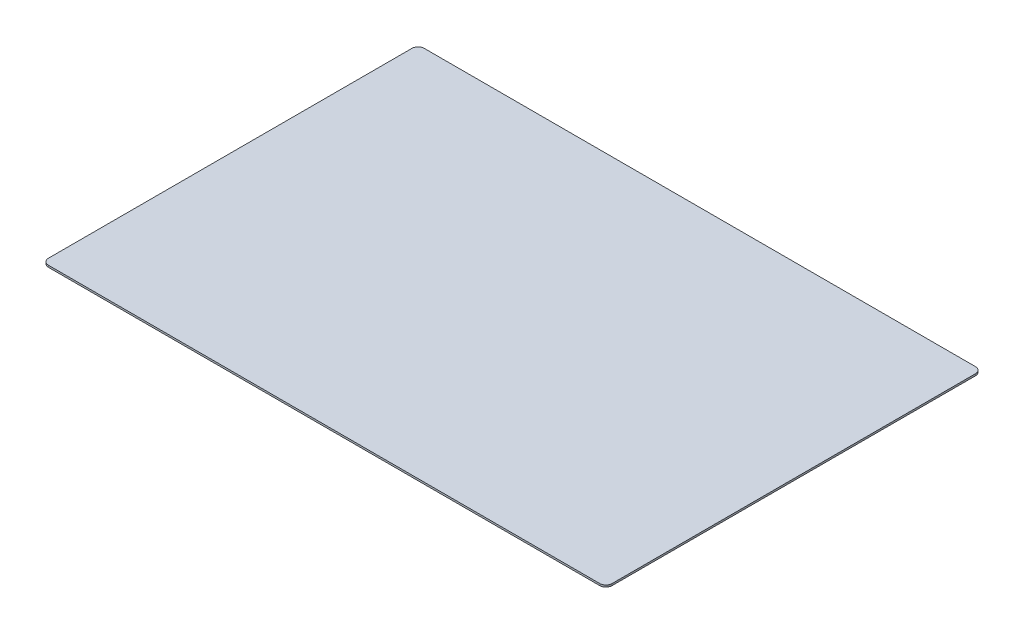
SolidWorks part; units mm, degrees
ref_plane "Front Plane" through (0, 0, 0) normal (0, 0, 1) x (1, 0, 0)
ref_plane "Top Plane" through (0, 0, 0) normal (0, 1, 0) x (1, 0, 0)
ref_plane "Right Plane" through (0, 0, 0) normal (1, 0, 0) x (0, 0, -1)
sketch "Sketch1" plane through (0, 0, 0) normal (0, 1, 0) x (1, 0, 0)
  line L1 (-457.2, 304.8) -> (457.2, 304.8)
  line L2 (-457.2, 304.8) -> (-457.2, -304.8)
  line L3 (-457.2, -304.8) -> (457.2, -304.8)
  line L4 (457.2, 304.8) -> (457.2, -304.8)
  line L5 (-457.2, 304.8) -> (457.2, -304.8) construction
  line L6 (-457.2, -304.8) -> (457.2, 304.8) construction
  point P0 (0, 0)
  dimension "D1" = 609.6
  dimension "D2" = 914.4
extrude "Boss-Extrude1" add sketch "Sketch1" along normal blind 3
fillet "Fillet1" radius 10 4 edges at (-457.2, 1.5, -304.8) (457.2, 1.5, -304.8) (457.2, 1.5, 304.8) (-457.2, 1.5, 304.8)
sketch "Sketch4" plane through (0, 0, 0) normal (0, -1, 0) x (-1, 0, 0)
  line L0 (357.2, -304.8) -> (357.2, 304.8) construction
  line L1 (447.2, -304.8) -> (-447.2, -304.8) construction
  line L2 (-447.2, 304.8) -> (447.2, 304.8) construction
  line L3 (-357.2, -304.8) -> (-357.2, 304.8) construction
  line L4 (457.2, 294.8) -> (457.2, -294.8) construction
  line L5 (-457.2, -294.8) -> (-457.2, 294.8) construction
  dimension "D1" = 100
  dimension "D2" = 100
